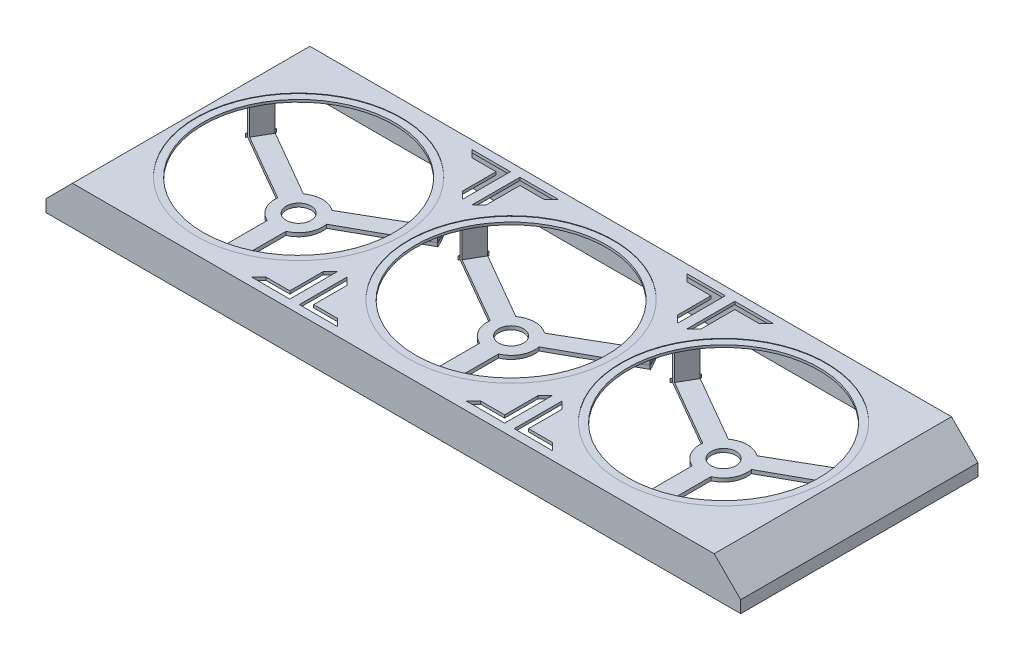
SolidWorks part; units mm, degrees
ref_plane "Front Plane" through (0, 0, 0) normal (0, 0, 1) x (1, 0, 0)
ref_plane "Top Plane" through (0, 0, 0) normal (0, 1, 0) x (1, 0, 0)
ref_plane "Right Plane" through (0, 0, 0) normal (1, 0, 0) x (0, 0, -1)
sketch "Sketch1" plane through (0, 0, 0) normal (0, 0, 1) x (1, 0, 0)
  line L0 (-48.7011, 0) -> (-146.6935, 0) construction
  line L1 (134.3816, 0) -> (-134.3816, 0)
  line L2 (-134.3816, 0) -> (-145.5, -11.1184)
  line L3 (-145.5, -11.1184) -> (-145.5, -16.2)
  line L4 (-145.5, -16.2) -> (-144.3, -16.2)
  line L5 (0, 2.7745) -> (0, -4.0056) construction
  line L6 (144.3, -11.6154) -> (133.8846, -1.2)
  line L7 (-144.3, -16.2) -> (-144.3, -11.6154)
  line L8 (-144.3, -11.6154) -> (-133.8846, -1.2)
  line L9 (-133.8846, -1.2) -> (133.8846, -1.2)
  line L11 (134.3816, 0) -> (145.5, -11.1184)
  line L12 (145.5, -11.1184) -> (145.5, -16.2)
  line L13 (145.5, -16.2) -> (144.3, -16.2)
  line L14 (144.3, -16.2) -> (144.3, -11.6154)
  dimension "D2" = 1.2
  dimension "D3" = 1.2
  dimension "D4" = 1.2
  dimension "D5" = 15
extrude "Boss-Extrude1" add sketch "Sketch1" along normal mid plane 97
sketch "Sketch2" plane through (0, 0, 48.5) normal (0, 0, 1) x (1, 0, 0)
  line L0 (-145.5, -16.2) -> (145.5, -16.2)
  line L1 (145.5, -16.2) -> (145.5, -11.1184)
  line L2 (145.5, -11.1184) -> (134.3816, 0)
  line L3 (134.3816, 0) -> (-134.3816, 0)
  line L4 (-134.3816, 0) -> (-145.5, -11.1184)
  line L5 (-145.5, -11.1184) -> (-145.5, -16.2)
  line L6 (-145.5, -16.2) -> (-145.5156, -16.2117)
  line M1 (-134.3816, 0) -> (-145.5, -11.1184)
  line M2 (-145.5, -11.1184) -> (-145.5, -16.2)
  line M3 (-145.5, -16.2) -> (-144.3, -16.2)
  line M4 (-144.3, -16.2) -> (-144.3, -11.6154)
  line M5 (-144.3, -11.6154) -> (-133.8846, -1.2)
  line M6 (-133.8846, -1.2) -> (133.8846, -1.2)
  line M7 (133.8846, -1.2) -> (144.3, -11.6154)
  line M8 (144.3, -11.6154) -> (144.3, -16.2)
  line M9 (144.3, -16.2) -> (145.5, -16.2)
  line M10 (145.5, -16.2) -> (145.5, -11.1184)
  line M11 (145.5, -11.1184) -> (134.3816, 0)
  line M12 (134.3816, 0) -> (-134.3816, 0)
extrude "Boss-Extrude2" add sketch "Sketch2" along normal blind 1.2 contours L0 M4 M8 M7 M6 M5 | M12 M1 M2 M3 M4 M5 M6 M7 M8 M9 M10 M11
mirror "Mirror1" about plane through (0, 0, 0) normal (0, 0, 1) of "Boss-Extrude2"
sketch "Sketch3" plane through (0, 0, 0) normal (0, 1, 0) x (1, 0, 0)
  line L0 (-134.3816, -49.7) -> (-134.3816, 49.7) construction
  line L2 (-134.3816, 0) -> (134.3816, 0) construction
  line L3 (134.3816, -49.7) -> (134.3816, 49.7) construction
  circle A0 centre (-89.3816, 0) radius 40
  circle A1 centre (-0.3816, 0) radius 40
  circle A2 centre (88.6184, 0) radius 40
  dimension "D1" = 80
  dimension "D2" = 45
  dimension "D3" = 3
extrude "Cut-Extrude1" cut sketch "Sketch3" against normal blind 1.2
sketch "Sketch4" plane through (0, 0, 0) normal (0, 1, 0) x (1, 0, 0)
  line L0 (27.0728, 46.2063) -> (43.1184, 46.2063)
  line L1 (-44.8816, 49.7) -> (-44.8816, -49.7) construction
  line L2 (134.3816, 49.7) -> (-134.3816, 49.7) construction
  line L4 (-62.9272, 46.2063) -> (-46.8816, 46.2063)
  line L5 (-46.8816, 46.2063) -> (-46.8816, 26.2063)
  line L6 (-46.8816, 26.2063) -> (-49.8816, 29.2063)
  line L7 (-49.8816, 29.2063) -> (-49.8816, 43.2063)
  line L8 (-49.8816, 43.2063) -> (-59.9272, 43.2063)
  line L9 (-59.9272, 43.2063) -> (-62.9272, 46.2063)
  line L10 (-42.8816, 26.2063) -> (-39.8816, 29.2063)
  line L11 (-29.836, 43.2063) -> (-26.836, 46.2063)
  line L12 (-26.836, 46.2063) -> (-42.8816, 46.2063)
  line L13 (-39.8816, 43.2063) -> (-29.836, 43.2063)
  line L14 (-39.8816, 29.2063) -> (-39.8816, 43.2063)
  line L15 (-42.8816, 46.2063) -> (-42.8816, 26.2063)
  line L16 (43.1184, 46.2063) -> (43.1184, 26.2063)
  line L17 (43.1184, 26.2063) -> (40.1184, 29.2063)
  line L18 (40.1184, 29.2063) -> (40.1184, 43.2063)
  line L19 (40.1184, 43.2063) -> (30.0728, 43.2063)
  line L20 (30.0728, 43.2063) -> (27.0728, 46.2063)
  line L21 (47.1184, 26.2063) -> (50.1184, 29.2063)
  line L22 (60.164, 43.2063) -> (63.164, 46.2063)
  line L23 (63.164, 46.2063) -> (47.1184, 46.2063)
  line L24 (50.1184, 43.2063) -> (60.164, 43.2063)
  line L25 (50.1184, 29.2063) -> (50.1184, 43.2063)
  line L26 (47.1184, 46.2063) -> (47.1184, 26.2063)
  line L27 (45.1184, 49.7) -> (45.1184, -49.7) construction
  line L28 (-134.3816, 0) -> (134.3816, 0) construction
  line L29 (-134.3816, -49.7) -> (-134.3816, 49.7) construction
  line L30 (134.3816, -49.7) -> (134.3816, 49.7) construction
  line L31 (47.1184, -46.2063) -> (47.1184, -26.2063)
  line L32 (50.1184, -29.2063) -> (50.1184, -43.2063)
  line L33 (50.1184, -43.2063) -> (60.164, -43.2063)
  line L34 (63.164, -46.2063) -> (47.1184, -46.2063)
  line L35 (60.164, -43.2063) -> (63.164, -46.2063)
  line L36 (47.1184, -26.2063) -> (50.1184, -29.2063)
  line L37 (30.0728, -43.2063) -> (27.0728, -46.2063)
  line L38 (40.1184, -43.2063) -> (30.0728, -43.2063)
  line L39 (40.1184, -29.2063) -> (40.1184, -43.2063)
  line L40 (43.1184, -26.2063) -> (40.1184, -29.2063)
  line L41 (43.1184, -46.2063) -> (43.1184, -26.2063)
  line L42 (27.0728, -46.2063) -> (43.1184, -46.2063)
  line L43 (-26.836, -46.2063) -> (-42.8816, -46.2063)
  line L44 (-29.836, -43.2063) -> (-26.836, -46.2063)
  line L45 (-39.8816, -43.2063) -> (-29.836, -43.2063)
  line L46 (-39.8816, -29.2063) -> (-39.8816, -43.2063)
  line L47 (-42.8816, -46.2063) -> (-42.8816, -26.2063)
  line L48 (-42.8816, -26.2063) -> (-39.8816, -29.2063)
  line L49 (-46.8816, -26.2063) -> (-49.8816, -29.2063)
  line L50 (-49.8816, -29.2063) -> (-49.8816, -43.2063)
  line L51 (-46.8816, -46.2063) -> (-46.8816, -26.2063)
  line L52 (-59.9272, -43.2063) -> (-62.9272, -46.2063)
  line L53 (-62.9272, -46.2063) -> (-46.8816, -46.2063)
  line L54 (-49.8816, -43.2063) -> (-59.9272, -43.2063)
  point P38 (45.1184, 0)
  dimension "D1" = 3
  dimension "D2" = 3
  dimension "D3" = 45
  dimension "D4" = 45
  dimension "D5" = 2
  dimension "D6" = 20
  dimension "D7" = 2
extrude "Cut-Extrude2" cut sketch "Sketch4" against normal blind 2
sketch "Sketch5" plane through (0, 0, 0) normal (0, 1, 0) x (1, 0, 0)
  circle A0 centre (-89.3816, 0) radius 43
  circle A1 centre (-0.3816, 0) radius 43
  circle A2 centre (88.6184, 0) radius 43
  dimension "D1" = 86
  dimension "D2" = 3
extrude "Cut-Extrude3" cut sketch "Sketch5" against normal blind 0.2
sketch "Sketch6" plane through (0, -1.2, 0) normal (0, -1, 0) x (1, 0, 0)
  line L0 (-55.4733, -24.1169) -> (-51.5416, -17.3071)
  line L1 (-85.45, 41.424) -> (-93.3133, 41.424)
  line L2 (-85.45, 41.424) -> (-85.45, 43.6252)
  line L3 (-85.45, 43.6252) -> (-93.3133, 43.6252)
  line L4 (-93.3133, 41.424) -> (-93.3133, 43.6252)
  line L5 (-85.45, 41.424) -> (-93.3133, 43.6252) construction
  line L6 (-85.45, 43.6252) -> (-93.3133, 41.424) construction
  line L7 (-51.5416, -17.3071) -> (-49.6353, -18.4077)
  line L8 (-53.5669, -25.2175) -> (-49.6353, -18.4077)
  line L9 (-55.4733, -24.1169) -> (-53.5669, -25.2175)
  line L10 (-127.2217, -17.3071) -> (-123.29, -24.1169)
  line L11 (-123.29, -24.1169) -> (-125.1963, -25.2175)
  line L12 (-129.128, -18.4077) -> (-125.1963, -25.2175)
  line L13 (-127.2217, -17.3071) -> (-129.128, -18.4077)
  circle A0 centre (-89.3816, 0) radius 42.5246
  point P3 (-89.3816, 42.5246)
  point P19 (-89.3816, 0)
  dimension "D1" = 3
extrude "Boss-Extrude3" add sketch "Sketch6" along normal blind 12 contours A0 L2 L3 L4 | L2 A0 L4 L1 | L13 A0 L11 L10 | A0 L13 L12 L11 | A0 L9 L8 L7 | L9 A0 L7 L0
sketch "Sketch7" plane through (0, -13.2, 0) normal (0, -1, 0) x (1, 0, 0)
  circle A0 centre (-89.3816, 0) radius 43.9741
extrude "Boss-Extrude4" add sketch "Sketch7" along normal blind 1.5 contours A0
sketch "Sketch8" plane through (0, -13.2, 0) normal (0, 1, 0) x (1, 0, 0)
  line L0 (-125.1963, 25.2175) -> (-95.3786, 8.0023)
  line L1 (-129.128, 18.4077) -> (-99.3103, 1.1924)
  line L2 (-53.5669, 25.2175) -> (-83.3847, 8.0023)
  line L3 (-49.6353, 18.4077) -> (-79.5571, 1.8652)
  line L4 (-93.3133, -43.6252) -> (-93.3133, -9.1947)
  line L5 (-85.45, -43.6252) -> (-85.45, -9.1947)
  circle A0 centre (-89.3816, 0) radius 5.2018
  arc A1 (-85.45, -9.1947) -> (-79.5571, 1.8652) centre (-89.3816, 0) ccw
  arc A2 (-129.128, 18.4077) -> (-93.3133, -43.6252) centre (-99.2927, -5.7222) ccw
  arc A3 (-99.3103, 1.1924) -> (-93.3133, -9.1947) centre (-89.3816, 0) ccw
  arc A4 (-83.3847, 8.0023) -> (-95.3786, 8.0023) centre (-89.3816, 0) ccw
  arc A5 (-85.45, -43.6252) -> (-49.6353, 18.4077) centre (-77.1651, -7.0532) ccw
  arc A6 (-125.1963, 25.2175) -> (-53.5669, 25.2175) centre (-89.3816, 8.5837) cw
  dimension "D1" = 20
extrude "Cut-Extrude5" cut sketch "Sketch8" against normal blind 1.5
pattern_linear "LPattern1" count 3 spacing 89 along (1, 0, 0) of "Boss-Extrude3", "Boss-Extrude4", "Cut-Extrude5"
